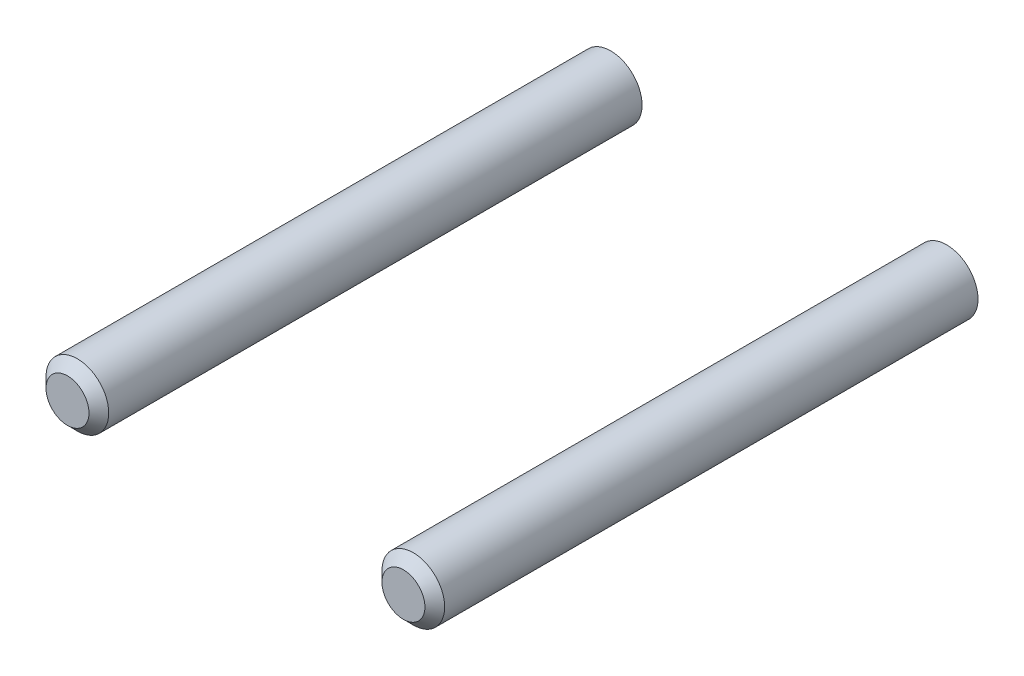
SolidWorks part; units mm, degrees
ref_plane "Front Plane" through (0, 0, 0) normal (0, 0, 1) x (1, 0, 0)
ref_plane "Top Plane" through (0, 0, 0) normal (0, 1, 0) x (1, 0, 0)
ref_plane "Right Plane" through (0, 0, 0) normal (1, 0, 0) x (0, 0, -1)
sketch "Sketch1" plane through (0, 0, 0) normal (0, 0, 1) x (1, 0, 0)
  circle A0 centre (-31.5065, 36.9034) radius 6.35
  circle A1 centre (36.523, 36.9034) radius 6.35
  circle A2 centre (36.523, -36.126) radius 6.35 construction
  circle A3 centre (-31.5065, -36.126) radius 6.35 construction
  dimension "D1" = 12.7
extrude "Boss-Extrude1" add sketch "Sketch1" along normal blind 20 and the other way blind 90
chamfer "Chamfer3" distance 2 angle 45 1 edges at (-25.1565, 36.9034, 20)
chamfer "Chamfer4" distance 2 angle 45 1 edges at (42.873, 36.9034, 20)
